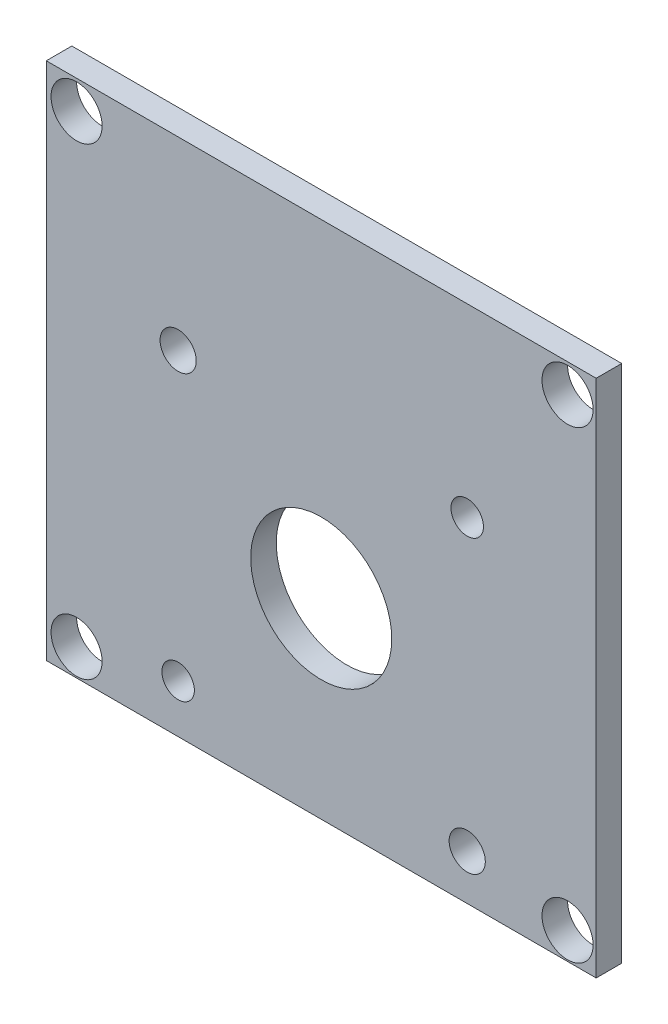
SolidWorks part; units mm, degrees
ref_plane "Front Plane" through (0, 0, 0) normal (0, 0, 1) x (1, 0, 0)
ref_plane "Top Plane" through (0, 0, 0) normal (0, 1, 0) x (1, 0, 0)
ref_plane "Right Plane" through (0, 0, 0) normal (1, 0, 0) x (0, 0, -1)
sketch "Sketch1" plane through (0, 0, 0) normal (0, 0, 1) x (1, 0, 0)
  line L1 (-34.163, -32.2707) -> (34.163, -32.2707)
  line L2 (-34.163, -32.2707) -> (-34.163, 32.2707)
  line L3 (-34.163, 32.2707) -> (34.163, 32.2707)
  line L4 (34.163, -32.2707) -> (34.163, 32.2707)
  line L5 (-34.163, -32.2707) -> (34.163, 32.2707) construction
  line L6 (-34.163, 32.2707) -> (34.163, -32.2707) construction
  line L17 (-30.3985, 28.7147) -> (30.607, 28.7147) construction
  line L18 (-30.3985, 28.7147) -> (-30.3985, -28.9117) construction
  line L19 (-30.3985, -28.9117) -> (30.607, -28.9117) construction
  line L20 (30.607, 28.7147) -> (30.607, -28.9117) construction
  circle A0 centre (-17.78, -26.2763) radius 2.0193
  circle A1 centre (18.1407, 9.2837) radius 2.0193
  circle A2 centre (-17.78, 9.2837) radius 2.2479
  circle A3 centre (18.141, -26.6373) radius 2.2479
  circle A4 centre (0, -8.4963) radius 8.763
  circle A5 centre (-30.3985, 28.7147) radius 3.175
  circle A6 centre (-30.3985, -28.9117) radius 3.175
  circle A7 centre (30.607, -28.9117) radius 3.175
  circle A8 centre (30.607, 28.7147) radius 3.175
  point P0 (0, 0)
  dimension "D7" = 4.0386
  dimension "D8" = 4.4958
  dimension "D9" = 17.526
  dimension "D10" = 3.556
  dimension "D6" = 16.383
  dimension "D12" = 6.35
  dimension "D5" = 22.987
  dimension "D4" = 50.8
  dimension "D13" = 35.9207
  dimension "D1" = 64.5414
  dimension "D2" = 68.326
  dimension "D3" = 35.56
  dimension "D11" = 3.556
extrude "Boss-Extrude1" add sketch "Sketch1" along normal blind 3.175
